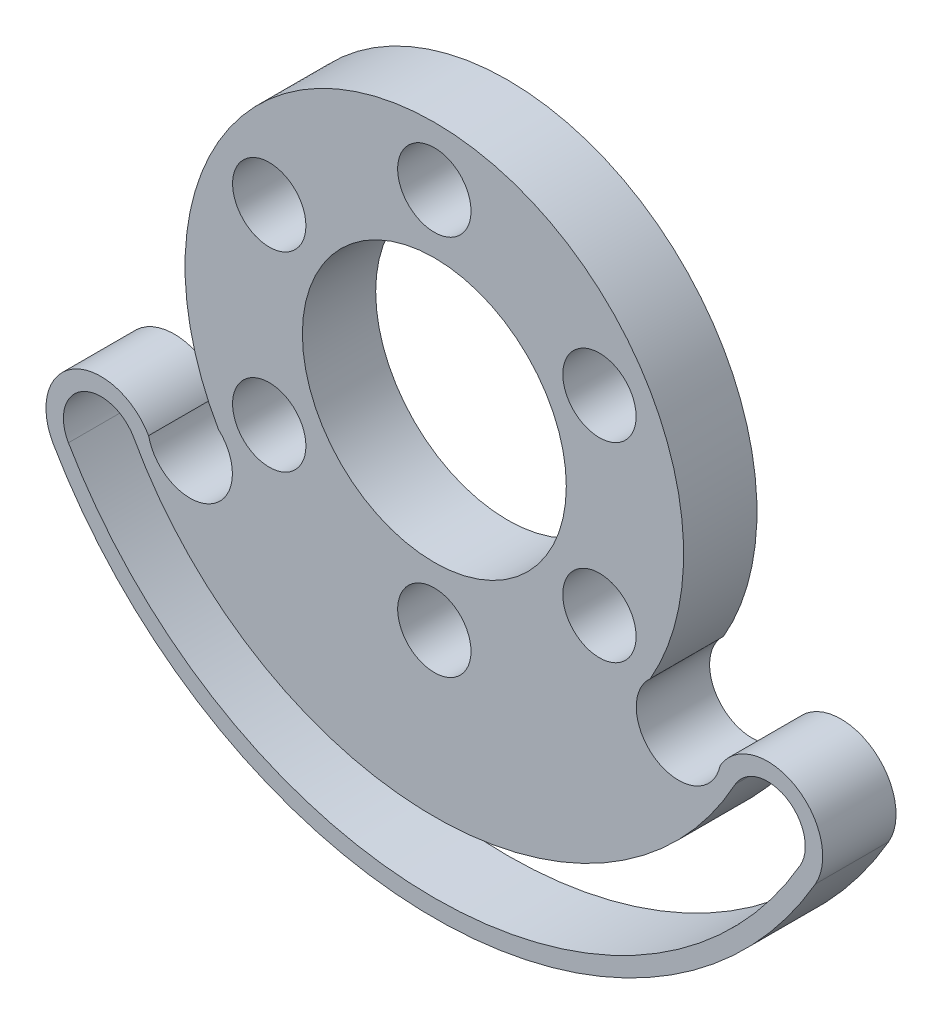
SolidWorks part; units mm, degrees
ref_plane "Front Plane" through (0, 0, 0) normal (0, 0, 1) x (1, 0, 0)
ref_plane "Top Plane" through (0, 0, 0) normal (0, 1, 0) x (1, 0, 0)
ref_plane "Right Plane" through (0, 0, 0) normal (1, 0, 0) x (0, 0, -1)
sketch "Sketch2" plane through (0, 0, 0) normal (0, 0, 1) x (1, 0, 0)
  line L0 (0, 0) -> (70.4683, -40.6849) construction
  line L1 (0, 0) -> (-71.5085, -41.2855) construction
  circle A0 centre (0, 0) radius 18
  circle A1 centre (0, 0) radius 34
  circle A2 centre (0, 0) radius 26
  circle A3 centre (0, 26) radius 5
  circle A4 centre (0, 0) radius 26
  circle A5 centre (22.5167, 13) radius 5
  circle A6 centre (0, 0) radius 26
  circle A7 centre (22.5167, -13) radius 5
  circle A8 centre (0, 0) radius 26
  circle A9 centre (0, -26) radius 5
  circle A10 centre (0, 0) radius 26
  circle A11 centre (-22.5167, -13) radius 5
  circle A12 centre (0, 0) radius 26
  circle A13 centre (-22.5167, 13) radius 5
  arc A14 (-38.9711, -22.5) -> (38.9711, -22.5) centre (0, 0) ccw
  arc A15 (-51.9615, -30) -> (51.9615, -30) centre (0, 0) ccw
  arc A16 (-51.9615, -30) -> (-38.9711, -22.5) centre (-45.4663, -26.25) cw
  arc A17 (38.9711, -22.5) -> (51.9615, -30) centre (45.4663, -26.25) cw
  arc A18 (-49.904, -28.8121) -> (-41.0287, -23.6879) centre (-45.4663, -26.25) cw
  arc A19 (41.0287, -23.6879) -> (49.904, -28.8121) centre (45.4663, -26.25) cw
  arc A20 (-41.0287, -23.6879) -> (41.0287, -23.6879) centre (0, -1.2849) ccw
  arc A21 (-49.904, -28.8121) -> (49.904, -28.8121) centre (0, 0) ccw
  arc A22 (-38.9711, -22.5) -> (-29.4449, -17) centre (-33.3219, -21.2848) ccw
  arc A23 (29.4449, -17) -> (38.9711, -22.5) centre (33.3194, -21.2891) ccw
  point P24 (0, 0)
  dimension "D1" = 68
  dimension "D2" = 36
  dimension "D3" = 52
  dimension "D4" = 10
  dimension "D6" = 90
  dimension "D7" = 120
  dimension "D9" = 5.78
  dimension "D8" = 120
  dimension "D5" = 6
extrude "Boss-Extrude1" add sketch "Sketch2" against normal blind 10 contours A23 A1 A22 A14 | A23 A1 A22 A13 A2 A3 A5 A7 A9 A11 | A13 A2 A11 A9 A7 A5 A3 A0 | A23 A14 A22 A16 A15 A17 A21 A18 A20 A19
